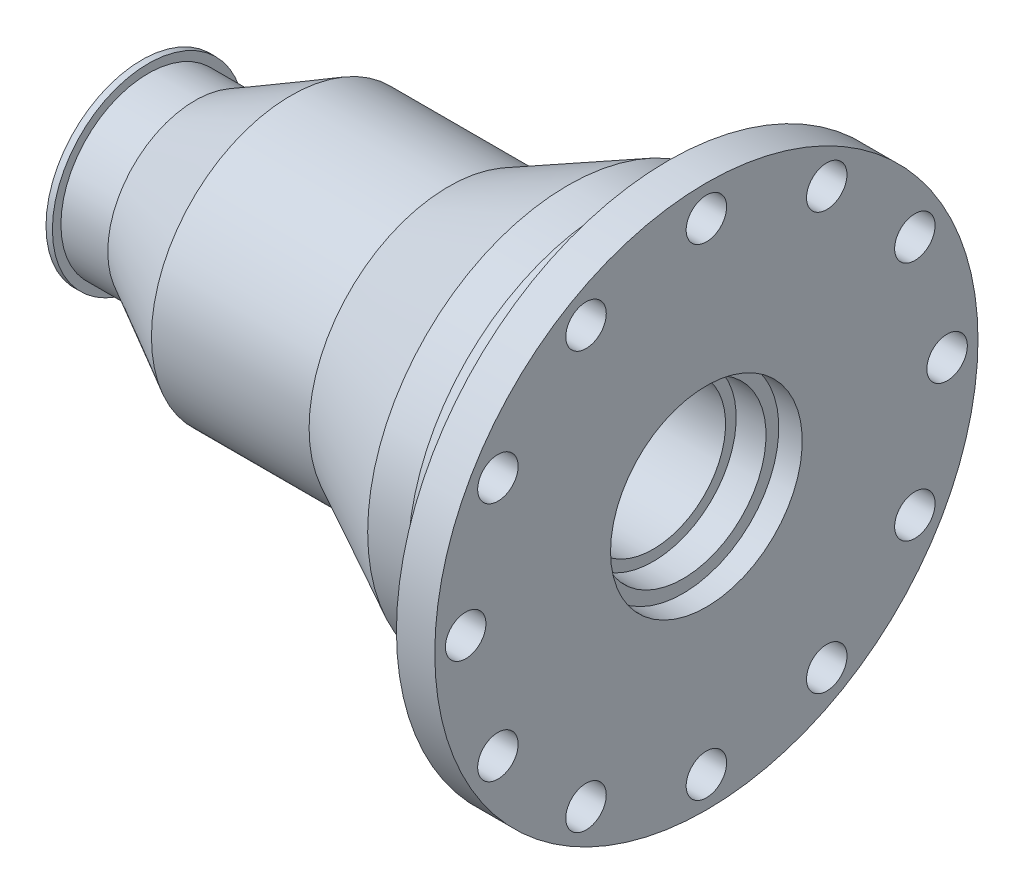
SolidWorks part; units mm, degrees
ref_plane "Спереди" through (0, 0, 0) normal (0, 0, 1) x (1, 0, 0)
ref_plane "Сверху" through (0, 0, 0) normal (0, 1, 0) x (1, 0, 0)
ref_plane "Справа" through (0, 0, 0) normal (1, 0, 0) x (0, 0, -1)
sketch "Эскиз1" plane through (0, 0, 0) normal (0, 0, 1) x (1, 0, 0)
  line L0 (0, 0) -> (265, 0)
  line L1 (0, 0) -> (0, 45)
  line L2 (0, 45) -> (3, 45)
  line L3 (3, 45) -> (3, 41)
  line L4 (3, 41) -> (25, 41)
  line L5 (25, 41) -> (70, 65.5)
  line L6 (70, 65.5) -> (144, 65.5)
  line L7 (144, 65.5) -> (200, 94)
  line L8 (200, 94) -> (220, 94)
  line L9 (220, 94) -> (220, 95)
  line L10 (220, 95) -> (239, 95)
  line L11 (239, 95) -> (239, 100)
  line L12 (239, 100) -> (247, 100)
  line L13 (247, 100) -> (247, 127.5)
  line L14 (247, 127.5) -> (265, 127.5)
  line L15 (265, 127.5) -> (265, 0)
revolve "Повернуть1" add sketch "Эскиз1" angle 360 about L0
sketch "Эскиз2" plane through (0, 0, 0) normal (0, 0, 1) x (1, 0, 0)
  line L0 (0, 0) -> (265, 0)
  line L1 (0, 0) -> (0, 31)
  line L2 (0, 31) -> (203.5, 31)
  line L3 (203.5, 31) -> (203.5, 34)
  line L4 (203.5, 34) -> (240, 34)
  line L5 (240, 34) -> (240, 39)
  line L6 (240, 39) -> (254, 39)
  line L7 (254, 39) -> (254, 45)
  line L8 (254, 45) -> (265, 45)
  line L9 (265, 45) -> (265, 0)
revolve "Вырез-Повернуть1" cut sketch "Эскиз2" angle 360 about L0
sketch "Эскиз3" plane through (0, 0, 0) normal (1, 0, 0) x (0, 0, -1)
  circle A0 centre (0, 113) radius 9.5
extrude "Вырез-Вытянуть1" cut sketch "Эскиз3" along normal through all
sketch "Эскиз4" plane through (0, 0, 0) normal (1, 0, 0) x (0, 0, -1)
  circle A0 centre (-56.5, 97.8609) radius 9.5
extrude "Вырез-Вытянуть2" cut sketch "Эскиз4" along normal through all
sketch "Эскиз5" plane through (0, 0, 0) normal (1, 0, 0) x (0, 0, -1)
  circle A0 centre (-97.8609, 56.5) radius 9.5
extrude "Вырез-Вытянуть3" cut sketch "Эскиз5" along normal through all
sketch "Эскиз6" plane through (0, 0, 0) normal (1, 0, 0) x (0, 0, -1)
  circle A0 centre (-113, 0) radius 9.5
extrude "Вырез-Вытянуть4" cut sketch "Эскиз6" along normal through all
sketch "Эскиз7" plane through (0, 0, 0) normal (1, 0, 0) x (0, 0, -1)
  circle A0 centre (-97.8609, -56.5) radius 9.5
extrude "Вырез-Вытянуть5" cut sketch "Эскиз7" along normal through all
sketch "Эскиз8" plane through (0, 0, 0) normal (1, 0, 0) x (0, 0, -1)
  circle A0 centre (-56.5, -97.8609) radius 9.5
extrude "Вырез-Вытянуть6" cut sketch "Эскиз8" along normal through all
sketch "Эскиз9" plane through (0, 0, 0) normal (1, 0, 0) x (0, 0, -1)
  circle A0 centre (0, -113) radius 9.5
extrude "Вырез-Вытянуть7" cut sketch "Эскиз9" along normal through all
sketch "Эскиз10" plane through (0, 0, 0) normal (1, 0, 0) x (0, 0, -1)
  circle A0 centre (56.5, -97.8609) radius 9.5
extrude "Вырез-Вытянуть8" cut sketch "Эскиз10" along normal through all
sketch "Эскиз11" plane through (0, 0, 0) normal (1, 0, 0) x (0, 0, -1)
  circle A0 centre (97.8609, -56.5) radius 9.5
extrude "Вырез-Вытянуть9" cut sketch "Эскиз11" along normal through all
sketch "Эскиз12" plane through (0, 0, 0) normal (1, 0, 0) x (0, 0, -1)
  circle A0 centre (113, 0) radius 9.5
extrude "Вырез-Вытянуть10" cut sketch "Эскиз12" along normal through all
sketch "Эскиз13" plane through (0, 0, 0) normal (1, 0, 0) x (0, 0, -1)
  circle A0 centre (97.8609, 56.5) radius 9.5
extrude "Вырез-Вытянуть11" cut sketch "Эскиз13" along normal through all
sketch "Эскиз14" plane through (0, 0, 0) normal (1, 0, 0) x (0, 0, -1)
  circle A0 centre (56.5, 97.8609) radius 9.5
extrude "Вырез-Вытянуть12" cut sketch "Эскиз14" along normal through all
